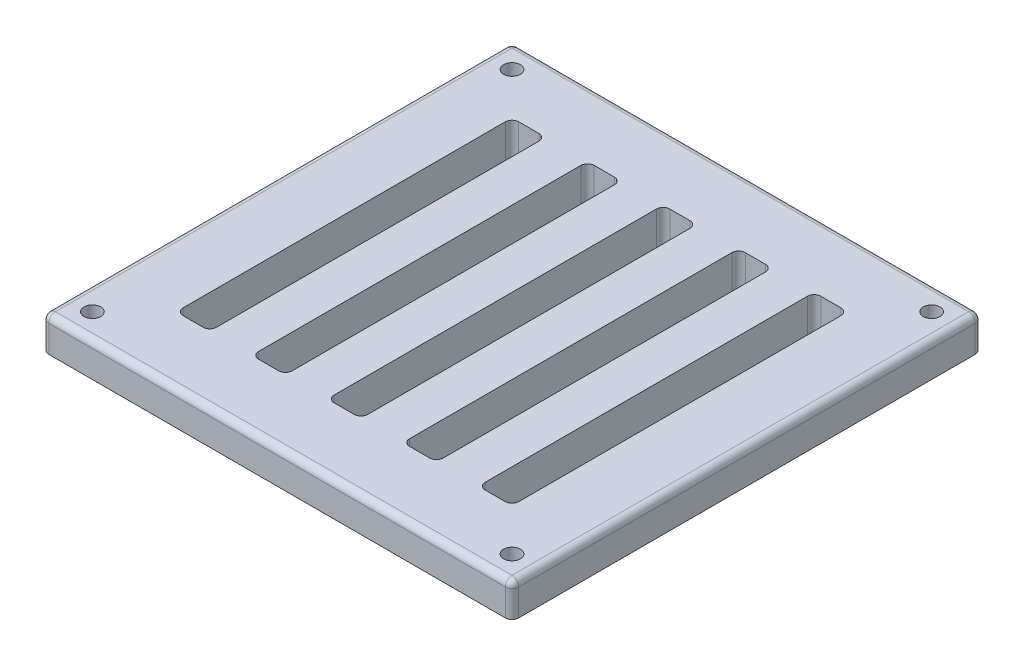
SolidWorks part; units mm, degrees
ref_plane "Front Plane" through (0, 0, 0) normal (0, 0, 1) x (1, 0, 0)
ref_plane "Top Plane" through (0, 0, 0) normal (0, 1, 0) x (1, 0, 0)
ref_plane "Right Plane" through (0, 0, 0) normal (1, 0, 0) x (0, 0, -1)
sketch "Sketch1" plane through (0, 0, 0) normal (0, 1, 0) x (1, 0, 0)
  line L1 (0, 0) -> (70, 0)
  line L2 (0, 0) -> (0, 70)
  line L3 (0, 70) -> (70, 70)
  line L4 (70, 0) -> (70, 70)
  dimension "D1" = 70
  dimension "D2" = 70
extrude "Boss-Extrude1" add sketch "Sketch1" along normal blind 5
sketch "Sketch2" plane through (0, 5, 0) normal (0, 1, 0) x (1, 0, 0)
  line L0 (0, 70) -> (0, 0) construction
  line L1 (0, 0) -> (70, 0) construction
  circle A0 centre (3.75, 3.75) radius 1.25
  dimension "D1" = 2.5
  dimension "D2" = 3.75
  dimension "D3" = 3.75
extrude "Cut-Extrude1" cut sketch "Sketch2" against normal through all
pattern_linear "LPattern1" count 2 spacing 62.5 along (1, 0, 0) of "Cut-Extrude1"
pattern_linear "LPattern2" count 2 spacing 62.5 along (0, 0, -1) of "LPattern1", "Cut-Extrude1"
sketch "Sketch3" plane through (0, 5, 0) normal (0, 1, 0) x (1, 0, 0)
  line L0 (0, 70) -> (0, 0) construction
  line L1 (10, 60) -> (15, 60)
  line L2 (10, 60) -> (10, 10)
  line L3 (10, 10) -> (15, 10)
  line L4 (15, 60) -> (15, 10)
  line L5 (70, 70) -> (0, 70) construction
  line L6 (0, 0) -> (70, 0) construction
  dimension "D1" = 5
  dimension "D2" = 10
  dimension "D3" = 10
  dimension "D4" = 10
extrude "Cut-Extrude2" cut sketch "Sketch3" against normal through all
fillet "Fillet2" radius 1 1 edges at (10, 2.5, -60)
fillet "Fillet3" radius 1 1 edges at (15, 2.5, -60)
fillet "Fillet4" radius 1 1 edges at (10, 2.5, -10)
fillet "Fillet5" radius 1 1 edges at (15, 2.5, -10)
pattern_linear "LPattern3" count 5 spacing 11.25 along (1, 0, 0) of "Fillet5", "Fillet4", "Fillet3", "Fillet2", "Cut-Extrude2"
fillet "Fillet6" radius 1 1 edges at (70, 2.5, 0)
fillet "Fillet7" radius 1 1 edges at (0, 2.5, 0)
fillet "Fillet8" radius 1 1 edges at (0, 2.5, -70)
fillet "Fillet9" radius 1 1 edges at (70, 2.5, -70)
fillet "Fillet10" radius 1 8 edges at (70, 5, -35) (69.7071, 5, -0.2929) (35, 5, 0) (0.2929, 5, -0.2929) (0, 5, -35) (0.2929, 5, -69.7071) (35, 5, -70) (69.7071, 5, -69.7071)
